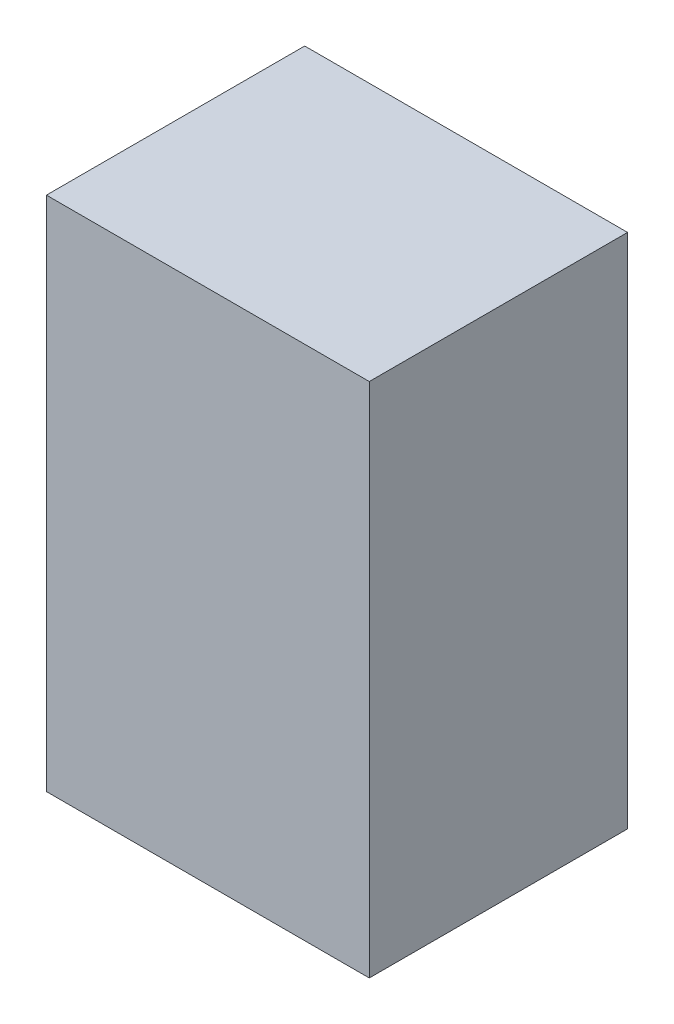
SolidWorks part; units mm, degrees
ref_plane "Front Plane" through (0, 0, 0) normal (1, 0, 0) x (0, 1, 0)
ref_plane "Top Plane" through (0, 0, 0) normal (0, 0, 1) x (0, 1, 0)
ref_plane "Right Plane" through (0, 0, 0) normal (0, 1, 0) x (-1, 0, 0)
sketch "Sketch1" plane through (0, 0, 0) normal (1, 0, 0) x (0, 1, 0)
  line L1 (-40, 20) -> (40, 20)
  line L2 (-40, 20) -> (-40, -20)
  line L3 (-40, -20) -> (40, -20)
  line L4 (40, 20) -> (40, -20)
  line L5 (-40, 20) -> (40, -20) construction
  line L6 (-40, -20) -> (40, 20) construction
  point P0 (0, 0)
  dimension "D1" = 80
  dimension "D2" = 40
extrude "Boss-Extrude1" add sketch "Sketch1" along normal blind 50
